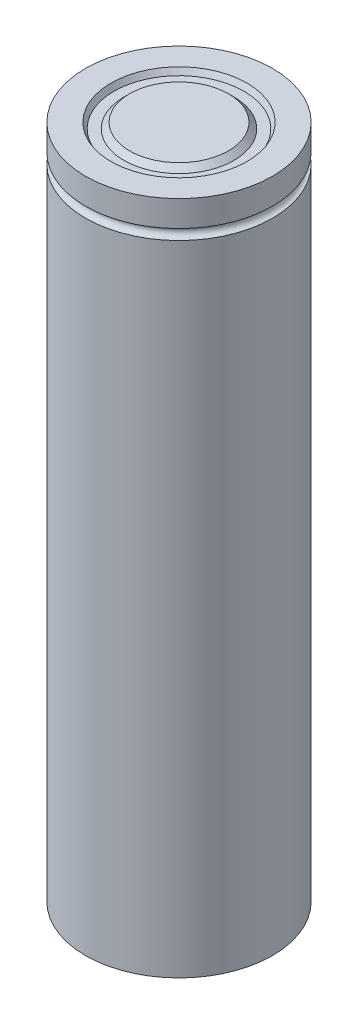
SolidWorks part; units mm, degrees
ref_plane "Front Plane" through (0, 0, 0) normal (0, 0, 1) x (1, 0, 0)
ref_plane "Top Plane" through (0, 0, 0) normal (0, 1, 0) x (1, 0, 0)
ref_plane "Right Plane" through (0, 0, 0) normal (1, 0, 0) x (0, 0, -1)
sketch "Sketch1" plane through (0, 0, 0) normal (0, 1, 0) x (1, 0, 0)
  circle A0 centre (0, 0) radius 9
  dimension "D1" = 18
extrude "Boss-Extrude1" add sketch "Sketch1" along normal blind 65
sketch "Sketch2" plane through (0, 0, 0) normal (1, 0, 0) x (0, 0, -1)
  line L0 (9, 0) -> (9, 65) construction
  line L1 (9, 65) -> (-9, 65) construction
  line L2 (0, 0) -> (0, 65.8627) construction
  line L3 (6.5487, 65) -> (6.2559, 64.4668)
  line L4 (6.2559, 64.4668) -> (5.2975, 64.4668)
  line L5 (5.2975, 64.4668) -> (4.7642, 65)
  line L6 (4.7642, 65) -> (6.5487, 65)
  circle A0 centre (9, 62) radius 0.5
  dimension "D1" = 1
  dimension "D2" = 3
revolve "Cut-Revolve1" cut sketch "Sketch2" angle 360 about L2
